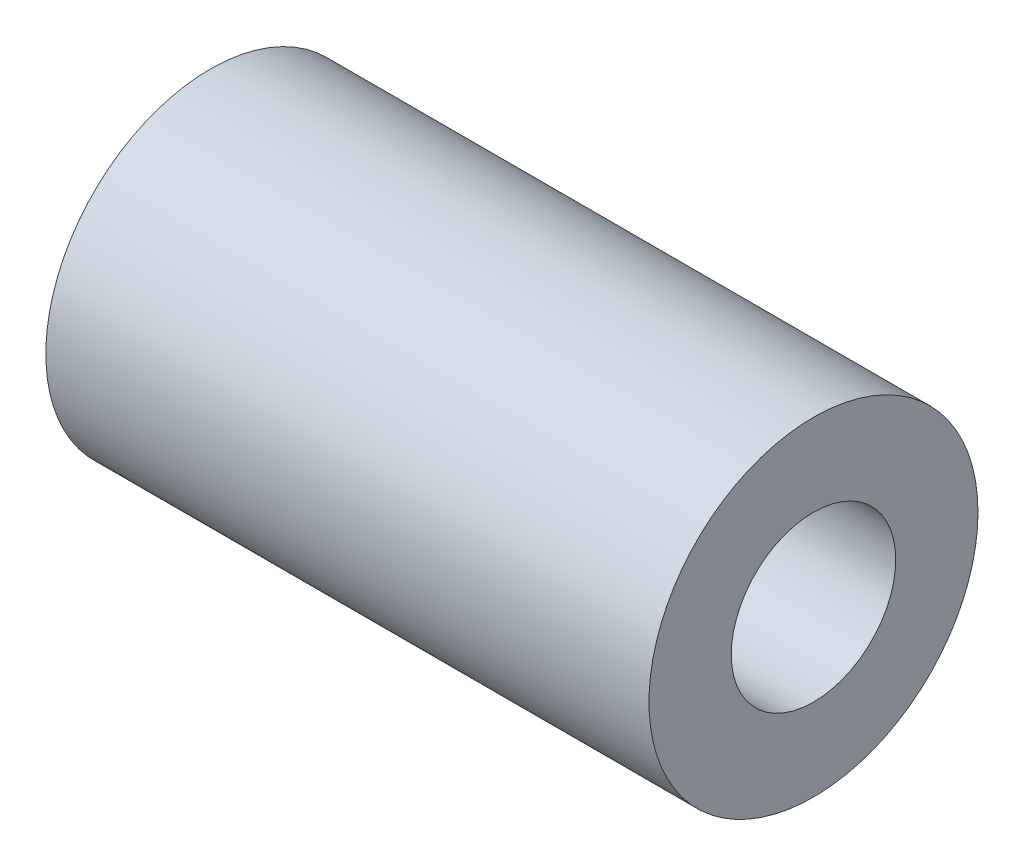
SolidWorks part; units mm, degrees
material "普通碳钢"
ref_plane "前视" through (0, 0, 0) normal (0, 0, 1) x (1, 0, 0)
ref_plane "上视" through (0, 0, 0) normal (0, 1, 0) x (1, 0, 0)
ref_plane "右视" through (0, 0, 0) normal (1, 0, 0) x (0, 0, -1)
sketch "草图1" plane through (0, 0, 0) normal (1, 0, 0) x (0, 0, -1)
  circle A0 centre (0, 0) radius 3
  circle A1 centre (0, 0) radius 1.5
  dimension "D1" = 6
  dimension "D2" = 3
extrude "凸台-拉伸1" add sketch "草图1" along normal blind 11
